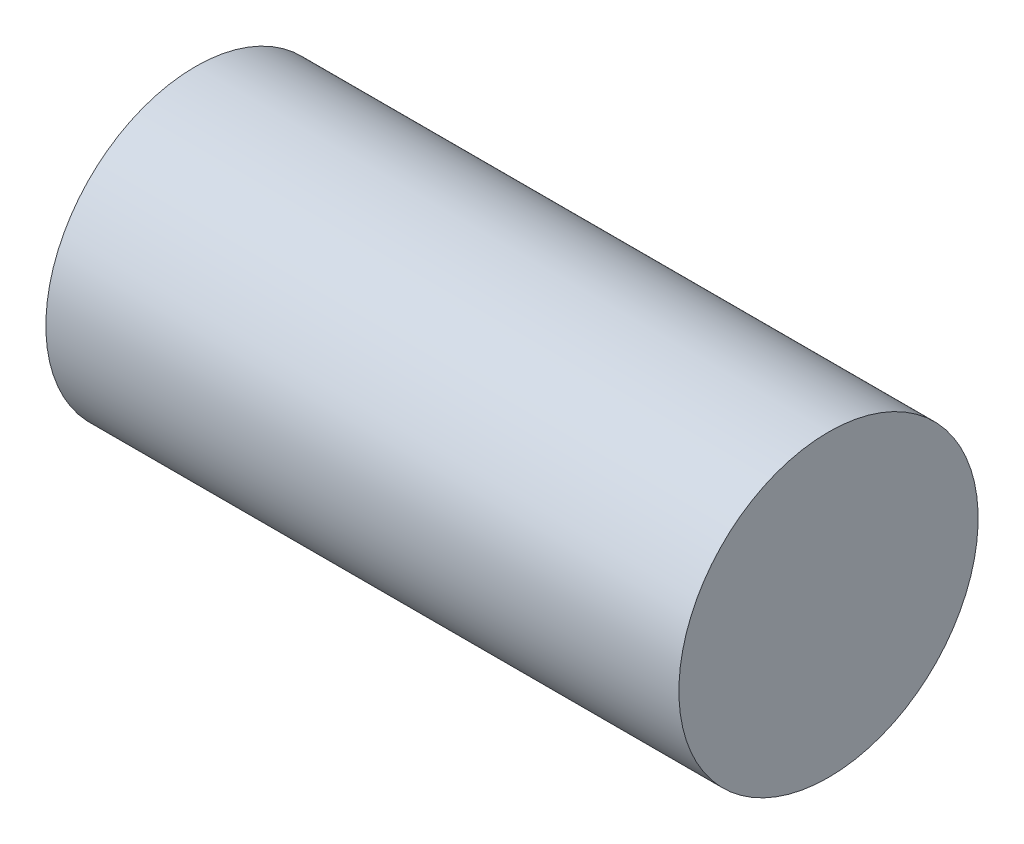
SolidWorks part; units mm, degrees
material "Alloy Steel"
ref_plane "Front Plane" through (0, 0, 0) normal (0, 0, 1) x (1, 0, 0)
ref_plane "Top Plane" through (0, 0, 0) normal (0, 1, 0) x (1, 0, 0)
ref_plane "Right Plane" through (0, 0, 0) normal (1, 0, 0) x (0, 0, -1)
sketch "Sketch1" plane through (0, 0, 0) normal (0, 0, 1) x (1, 0, 0)
  line L0 (0, 0) -> (0, 130)
  line L1 (0, 130) -> (550, 130)
  line L2 (550, 130) -> (550, 0)
  line L3 (550, 0) -> (0, 0) construction
  line L4 (0, 0) -> (550, 0)
  dimension "D1" = 260
  dimension "D2" = 550
revolve "Revolve1" add sketch "Sketch1" angle 360 about L3
